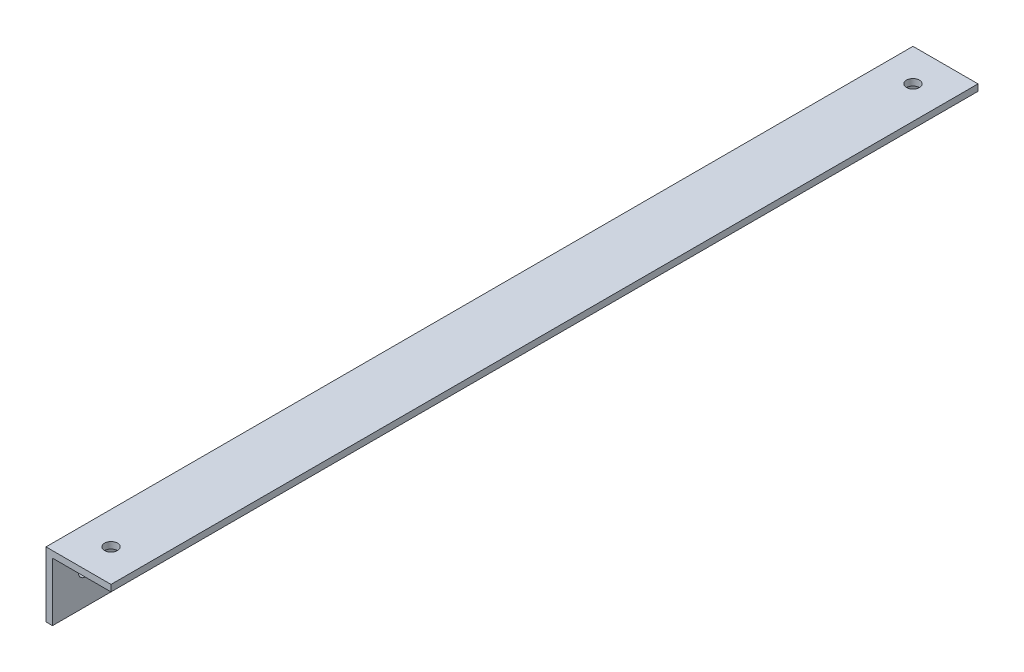
SolidWorks part; units mm, degrees
ref_plane "Front Plane" through (0, 0, 0) normal (0, 0, 1) x (1, 0, 0)
ref_plane "Top Plane" through (0, 0, 0) normal (0, 1, 0) x (1, 0, 0)
ref_plane "Right Plane" through (0, 0, 0) normal (1, 0, 0) x (0, 0, -1)
sketch "Sketch1" plane through (0, 0, 0) normal (0, 0, 1) x (1, 0, 0)
  line L0 (0, 0) -> (-27, 0)
  line L1 (-27, 0) -> (-27, -27)
  dimension "D1" = 27
  dimension "D2" = 27
extrude "Extrude-Thin1" add sketch "Sketch1" along normal blind 400 thin
sketch "Sketch2" plane through (0, 3, 0) normal (0, 1, 0) x (1, 0, 0)
  line L5 (-12.8787, -12.8787) -> (-17.1213, -17.1213) construction
  circle A0 centre (-15, -15) radius 3
  dimension "D2" = 6
extrude "Cut-Extrude1" cut sketch "Sketch2" against normal blind 10
pattern_linear "LPattern1" count 2 spacing 370 along (0, 0, 1) of "Cut-Extrude1"
sketch "Sketch3" plane through (-30, 0, 0) normal (-1, 0, 0) x (0, 0, 1)
  line L5 (12.8787, -9.8787) -> (17.1213, -14.1213) construction
  circle A0 centre (15, -12) radius 3
  dimension "D2" = 6
extrude "Cut-Extrude2" cut sketch "Sketch3" against normal blind 10
pattern_linear "LPattern2" count 2 spacing 370 along (0, 0, 1) of "Cut-Extrude2"
